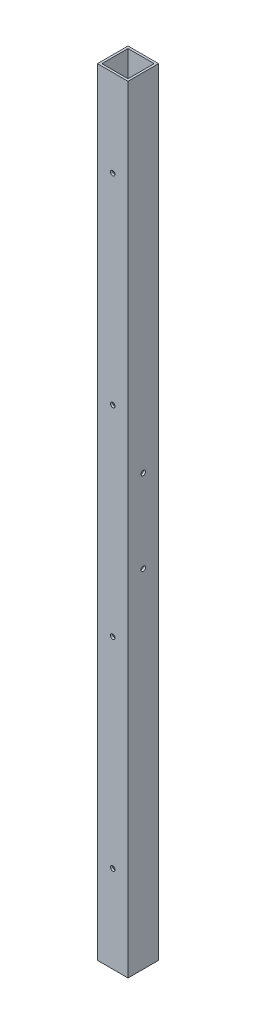
SolidWorks part; units mm, degrees
material "6061 Alloy"
ref_plane "Front Plane" through (0, 0, 0) normal (0, 0, 1) x (1, 0, 0)
ref_plane "Top Plane" through (0, 0, 0) normal (0, 1, 0) x (1, 0, 0)
ref_plane "Right Plane" through (0, 0, 0) normal (1, 0, 0) x (0, 0, -1)
sketch "Sketch1" plane through (0, 0, 0) normal (0, 1, 0) x (1, 0, 0)
  line L0 (-19.05, -19.05) -> (19.05, -19.05)
  line L1 (-22.225, -22.225) -> (22.225, -22.225)
  line L2 (-22.225, -22.225) -> (-22.225, 22.225)
  line L3 (-22.225, 22.225) -> (22.225, 22.225)
  line L4 (22.225, -22.225) -> (22.225, 22.225)
  line L5 (-22.225, -22.225) -> (22.225, 22.225) construction
  line L6 (-22.225, 22.225) -> (22.225, -22.225) construction
  line L7 (19.05, -19.05) -> (19.05, 19.05)
  line L8 (-19.05, 19.05) -> (19.05, 19.05)
  line L9 (-19.05, -19.05) -> (-19.05, 19.05)
  point P0 (0, 0)
  dimension "D1" = 44.45
  dimension "D2" = 3.175
extrude "Boss-Extrude1" add sketch "Sketch1" along normal blind 1130.3
hole_wizard "1/4 Clearance Hole1" positions "Sketch2" profile "Sketch3" hole size "1/4" standard "ANSI Inch" end condition through all
sketch "Sketch2" plane through (0, 0, 22.225) normal (0, 0, 1) x (1, 0, 0)
  line L0 (22.225, 565.15) -> (-22.225, 565.15) construction
  line L1 (22.225, 1130.3) -> (22.225, 0) construction
  line L2 (-22.225, 1130.3) -> (-22.225, 0) construction
  line L3 (22.225, 565.15) -> (22.225, 1130.3) construction
  line L4 (22.225, 847.725) -> (-22.225, 847.725) construction
  line L5 (-22.225, 0) -> (22.225, 0) construction
  line L6 (0, 1130.3) -> (0, 0) construction
  line L7 (-22.225, 1130.3) -> (22.225, 1130.3) construction
  point P15 (0, 1003.3)
  point P19 (0, 711.2)
  point P21 (0, 419.1)
  point P22 (0, 127)
  point P33 (0, 1054.1)
  point P34 (0, 703.7766)
  point P35 (0, 747.1886)
  dimension "D1" = 127
  dimension "D2" = 292.1
  dimension "D3" = 292.1
sketch "Sketch3" plane through (0, 127, 22.225) normal (1, 0, 0) x (0, -1, 0)
  line L0 (0, 0) -> (0, 44.45)
  line L1 (0, 44.45) -> (3.3782, 44.45)
  line L2 (3.3782, 44.45) -> (3.3782, 0)
  line L5 (3.3782, 0) -> (0, 0)
  line L11 (0, -6.35) -> (0, 107.95) construction
  dimension "Thru Hole Dia." = 6.7564
  dimension "Thru Hole Depth" = 44.45
hole_wizard "1/4 Clearance Hole2" positions "Sketch4" profile "Sketch5" hole size "1/4" standard "ANSI Inch" end condition through all
sketch "Sketch4" plane through (22.225, 0, 0) normal (1, 0, 0) x (0, 0, -1)
  line L0 (22.225, 565.15) -> (-22.225, 565.15) construction
  line L1 (22.225, 1130.3) -> (22.225, 0) construction
  line L2 (-22.225, 1130.3) -> (-22.225, 0) construction
  line L3 (0, 1130.3) -> (0, 0) construction
  line L4 (-22.225, 1130.3) -> (22.225, 1130.3) construction
  point P0 (0, 625.475)
  point P2 (0, 504.825)
  point P19 (0, 625.475)
  dimension "D1" = 120.65
sketch "Sketch5" plane through (22.225, 625.475, 0) normal (0, 1, 0) x (0, 0, -1)
  line L0 (0, 0) -> (0, 44.45)
  line L1 (0, 44.45) -> (3.3782, 44.45)
  line L2 (3.3782, 44.45) -> (3.3782, 0)
  line L5 (3.3782, 0) -> (0, 0)
  line L11 (0, -6.35) -> (0, 107.95) construction
  dimension "Thru Hole Dia." = 6.7564
  dimension "Thru Hole Depth" = 44.45
